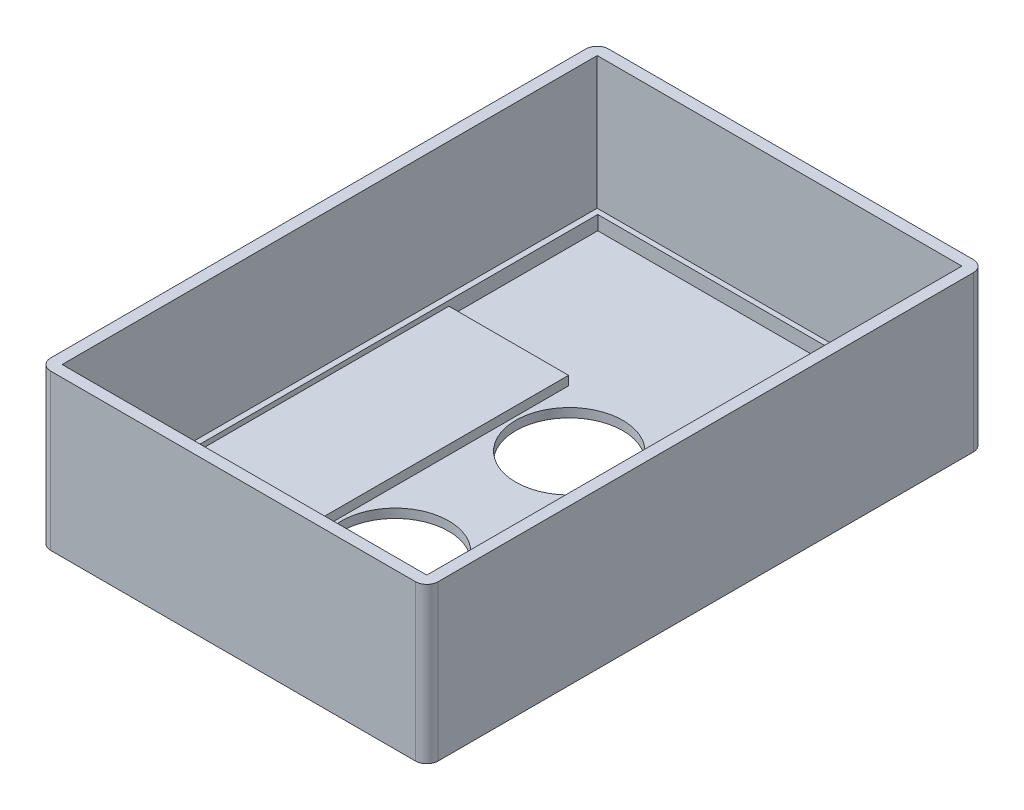
SolidWorks part; units mm, degrees
material "ABS"
ref_plane "Front Plane" through (0, 0, 0) normal (0, 0, 1) x (1, 0, 0)
ref_plane "Top Plane" through (0, 0, 0) normal (0, 1, 0) x (1, 0, 0)
ref_plane "Right Plane" through (0, 0, 0) normal (1, 0, 0) x (0, 0, -1)
sketch "Sketch1" plane through (0, 0, 0) normal (0, 1, 0) x (1, 0, 0)
  line L1 (86.36, 124.333) -> (0, 124.333)
  line L2 (86.36, 124.333) -> (86.36, 0)
  line L3 (86.36, 0) -> (0, 0)
  line L4 (0, 124.333) -> (0, 0)
extrude "Boss-Extrude1" add sketch "Sketch1" along normal blind 34.6202
sketch "Sketch3" plane through (0, 34.6202, 0) normal (0, 1, 0) x (1, 0, 0)
  line L1 (82.55, 120.65) -> (3.81, 120.65)
  line L2 (82.55, 120.65) -> (82.55, 3.81)
  line L3 (82.55, 3.81) -> (3.81, 3.81)
  line L4 (3.81, 120.65) -> (3.81, 3.81)
  line L5 (82.55, 120.65) -> (3.81, 3.81) construction
  line L6 (82.55, 3.81) -> (3.81, 120.65) construction
  point P0 (43.18, 62.23)
extrude "Cut-Extrude1" cut sketch "Sketch3" against normal blind 30.5816
sketch "Sketch4" plane through (0, 34.6202, 0) normal (0, 1, 0) x (1, 0, 0)
  line L1 (83.82, 121.793) -> (2.54, 121.793)
  line L2 (83.82, 121.793) -> (83.82, 2.54)
  line L3 (83.82, 2.54) -> (2.54, 2.54)
  line L4 (2.54, 121.793) -> (2.54, 2.54)
  line L5 (83.82, 121.793) -> (2.54, 2.54) construction
  line L6 (83.82, 2.54) -> (2.54, 121.793) construction
  point P0 (43.18, 62.1665)
extrude "Cut-Extrude2" cut sketch "Sketch4" against normal blind 29.464
sketch "Sketch6" plane through (0, 4.0386, 0) normal (0, 1, 0) x (1, 0, 0)
  line L0 (82.55, 3.81) -> (82.55, 120.65) construction
  line L1 (3.81, 120.65) -> (82.55, 120.65)
  line L2 (3.81, 120.65) -> (3.81, 87.472)
  line L3 (30.48, 87.472) -> (3.81, 87.472)
  line L4 (82.55, 120.65) -> (82.55, 87.472)
  line L5 (3.81, 3.81) -> (82.55, 3.81) construction
  line L6 (55.88, 87.472) -> (82.55, 87.472)
  line L7 (30.48, 87.472) -> (30.48, 3.81)
  line L8 (30.48, 3.81) -> (55.88, 3.81)
  line L9 (55.88, 87.472) -> (55.88, 3.81)
extrude "Cut-Extrude3" cut sketch "Sketch6" against normal blind 2.032
sketch "Sketch8" plane through (0, 2.0066, 0) normal (0, 1, 0) x (1, 0, 0)
  circle A0 centre (43.18, 36.1188) radius 11.938
  circle A1 centre (43.18, 74.93) radius 11.938
extrude "Cut-Extrude4" cut sketch "Sketch8" against normal blind 2.032
fillet "Fillet1" radius 2.54 4 edges at (86.36, 17.3101, 0) (0, 17.3101, 0) (0, 17.3101, -124.333) (86.36, 17.3101, -124.333)
